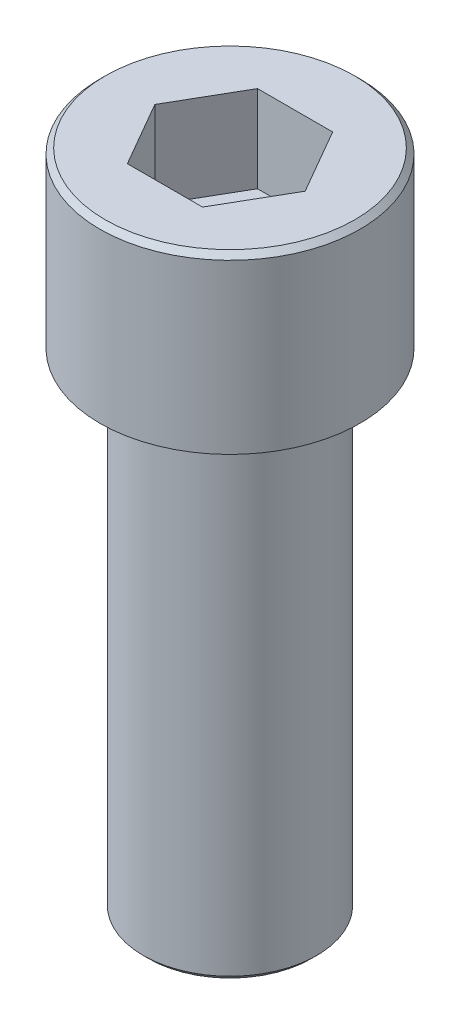
SolidWorks part; units mm, degrees
material "ASTM A574M"
ref_plane "Front" through (0, 0, 0) normal (0, 0, 1) x (1, 0, 0)
ref_plane "Base" through (0, 0, 0) normal (0, 1, 0) x (1, 0, 0)
ref_plane "Side" through (0, 0, 0) normal (1, 0, 0) x (0, 0, -1)
sketch "Sketch1" plane through (0, 0, 0) normal (0, 0, 1) x (1, 0, 0)
  line L0 (0, 0) -> (0, 28.4946) construction
  line L1 (0, 0) -> (8, 0)
  line L2 (8, 0) -> (8, 45)
  line L3 (8, 45) -> (12, 45)
  line L4 (12, 45) -> (12, 61)
  line L5 (12, 61) -> (0, 61)
  line L6 (0, 0) -> (0, 61)
  dimension "SCREW DIA" = 16
  dimension "HEAD DEPTH" = 16
  dimension "HEAD DIA" = 24
  dimension "SCREW LENGTH" = 45
revolve "Base-Revolve" add sketch "Sketch1" angle 360 about L0
sketch "Sketch2" plane through (0, 61, 0) normal (0, 1, 0) x (-1, 0, 0)
  line L0 (0, -4.7746) -> (0, 5.832) construction
  line L1 (5.9512, 0) -> (-5.4353, 0) construction
  line L2 (3.4641, -6) -> (-3.4641, -6)
  line L3 (-3.4641, -6) -> (-6.9282, 0)
  line L4 (3.4641, -6) -> (6.9282, 0)
  line L5 (3.4641, 6) -> (6.9282, 0)
  line L6 (-3.4641, 6) -> (-6.9282, 0)
  line L7 (3.4641, 6) -> (-3.4641, 6)
  dimension "HEX CUT LENGTH" = 12
  dimension "D2" = 120
extrude "Cut-Extrude1" cut sketch "Sketch2" against normal blind 8
chamfer "Chamfer1" distance 0.5 angle 45 2 edges at (0, 61, -12) (0, 0, -8)
sketch "Sketch3" plane through (0, 53, 0) normal (0, 1, 0) x (1, 0, 0)
  line L0 (-5.1962, -3) -> (5.1962, -3) construction
  line L1 (-3.4641, -6) -> (-6.9282, 0) construction
  line L2 (3.4641, -6) -> (6.9282, 0) construction
  text T0 "8.8 " font "Century Gothic" height 2.5
extrude "Cut-Extrude2" cut sketch "Sketch3" against normal blind 0.1
